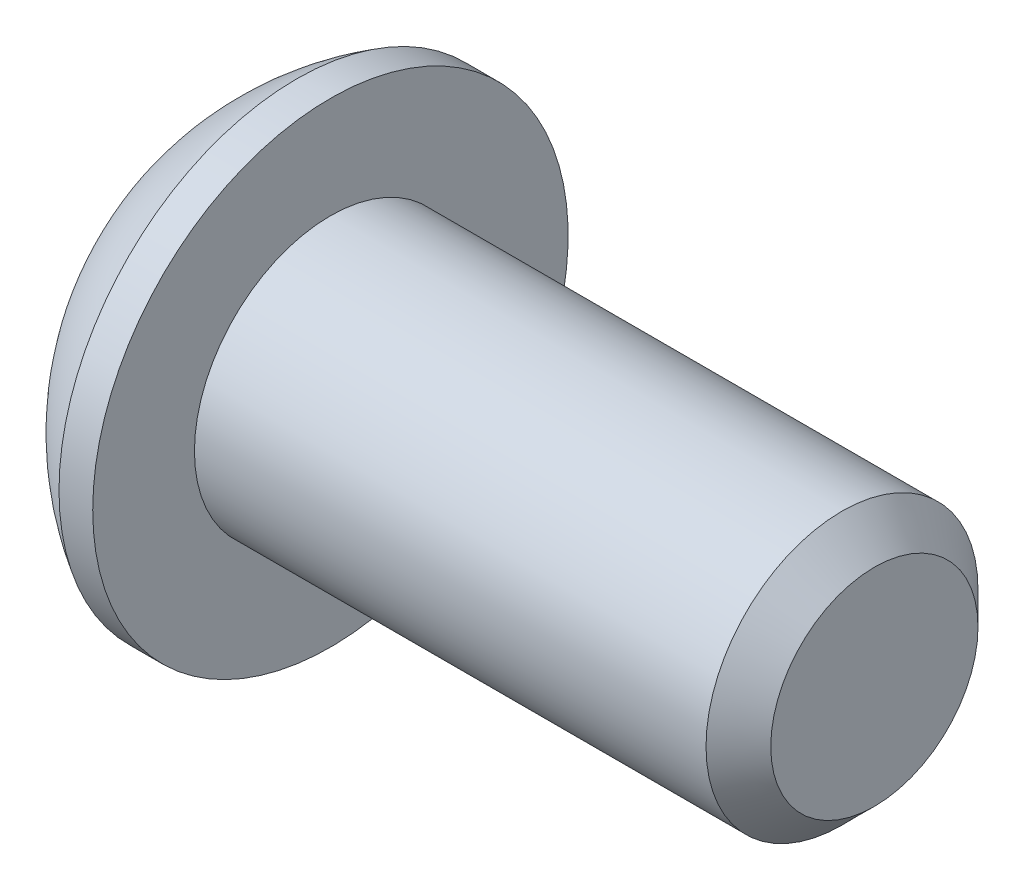
SolidWorks part; units mm, degrees
ref_plane "Plane1" through (0, 0, 0) normal (0, 0, 1) x (1, 0, 0)
ref_plane "Plane2" through (0, 0, 0) normal (0, 1, 0) x (1, 0, 0)
ref_plane "Plane3" through (0, 0, 0) normal (1, 0, 0) x (0, 0, -1)
sketch "BodySke" plane through (0, 0, 0) normal (0, 0, 1) x (1, 0, 0)
  line L0 (16.0528, 0) -> (16.0528, 2.4193)
  line L1 (15.2971, 3.175) -> (3.3528, 3.175)
  line L2 (3.3528, 3.175) -> (3.3528, 5.5499)
  line L3 (3.3528, 5.5499) -> (2.5654, 5.5499)
  line L4 (0, 0) -> (101.6, 0) construction
  line L5 (3.3528, -5.5499) -> (2.5654, -5.5499) construction
  line L6 (55.6768, -3.175) -> (3.3528, -3.175) construction
  line L7 (16.0528, 0) -> (0, 0)
  line L8 (0, 2.775) -> (0, -2.775) construction
  line L9 (0, 0) -> (0, 2.775)
  line L10 (16.0528, 2.4193) -> (15.2971, 3.175)
  line L11 (16.0528, -2.4193) -> (15.2971, -3.175) construction
  line L12 (4.6228, 9.525) -> (4.6228, -3.175) construction
  line L13 (3.3528, 9.525) -> (3.3528, -3.175) construction
  arc A1 (0, 2.775) -> (2.5654, 5.5499) centre (5.7851, 0) cw
  dimension "D1" = 5.5499
  dimension "Diameter" = 6.35
  dimension "Length" = 12.7
  dimension "Head_dia" = 11.0998
  dimension "Head_ht" = 3.3528
  dimension "Head_side_ht" = 0.7874
  dimension "Minor_dia" = 4.8387
  dimension "Body_ch_ang" = 45
  dimension "Advance" = 1.27
  dimension "Thread_nom" = 12.7
revolve "BaseBody" add sketch "BodySke" angle 360 about L4
cosmetic thread "ThreadCosmetic" [suppressed] parameters "Thread_length"=11.43, "Thread_minor"=4.8387
sketch "Sketch2" plane through (0, 0, 0) normal (0, 0, 1) x (1, 0, 0)
  line L0 (0, 1.9812) -> (2.2098, 1.9812)
  line L1 (2.2098, 1.9812) -> (3.3536, 0)
  line L3 (3.3536, 0) -> (0, 0)
  line L4 (0, 0) -> (0, 1.9812)
  line L5 (0, -1.9812) -> (2.2098, -1.9812) construction
  line L6 (0, 0) -> (47.625, 0) construction
  dimension "D2" = 60
  dimension "PreBroach_depth" = 2.2098
  dimension "PreBroach_dia" = 3.9624
revolve "PreBroach" cut sketch "Sketch2" angle 360 about L6
sketch "Sketch3" plane through (0, 0, 0) normal (1, 0, 0) x (0, 0, -1)
  line L0 (-1.9812, -1.1438) -> (-1.9812, 1.1438)
  line L1 (-1.9812, 1.1438) -> (0, 2.2877)
  line L2 (0, 2.2877) -> (1.9812, 1.1438)
  line L3 (1.9812, 1.1438) -> (1.9812, -1.1438)
  line L4 (1.9812, -1.1438) -> (0, -2.2877)
  line L5 (0, -2.2877) -> (-1.9812, -1.1438)
  dimension "D1" = 1.9812
  dimension "D2" = 1.9812
  dimension "D3" = 3.9624
  dimension "Hex_size" = 3.9624
extrude "Hex" cut sketch "Sketch3" along normal blind 2.2098
sketch "Sketch4" plane through (0, 9.525, 0) normal (1, 0, 0) x (0, 0, -1)
  line L0 (0, -9.525) -> (2.3876, -9.525)
  line L1 (0, -9.525) -> (6.1484, -5.9752) construction
  line L2 (0, -9.525) -> (1.1938, -7.4573)
  line L3 (1.9883, -8.949) -> (2.2704, -8.7861)
  line L4 (1.493, -8.0911) -> (1.7751, -7.9282)
  arc A0 (1.9883, -8.949) -> (1.493, -8.0911) centre (0, -9.525) ccw
  arc A1 (2.3876, -9.525) -> (2.2704, -8.7861) centre (0, -9.525) ccw
  arc A2 (1.1938, -7.4573) -> (1.7751, -7.9282) centre (0, -9.525) cw
  dimension "D1" = 30
  dimension "Spline_n_dim" = 4.1402
  dimension "Spline_m_dim" = 4.7752
  dimension "D2" = 60
  dimension "D3" = 0.4953
  dimension "Spline_p_dim" = 0.9906
extrude "Spline" [suppressed] cut sketch "Sketch4" along normal blind 2.2098
pattern_circular "CirPattern1" [suppressed] count 6 every 60 about axis through (0, 0, 0) along (1, 0, 0)
sketch "ThdSchSke" plane through (0, 0, 0) normal (0, 0, 1) x (1, 0, 0)
  line L0 (4.6228, -2.4193) -> (4.0937, -3.175)
  line L1 (4.6228, -2.4193) -> (5.1519, -3.175)
  line L2 (5.1519, -3.175) -> (5.1519, -3.9688)
  line L3 (-3.175, 0) -> (5.1513, 0) construction
  line L5 (5.1519, -3.9688) -> (4.0937, -3.9688)
  line L6 (4.0937, -3.9688) -> (4.0937, -3.175)
  dimension "Thread_minor" = 4.8387
  dimension "Diameter" = 6.35
  dimension "Start" = 4.6228
  dimension "SideAngle" = 55
  dimension "VeeAngle" = 70
  dimension "Overcut" = 7.9375
revolve "ThreadSchematic" [suppressed] cut sketch "ThdSchSke" angle 360 about L3
pattern_linear "ThdSchPat" [suppressed]
equation "\"D1@BodySke\" = \"Head_dia@BodySke\" * .5"
equation "\"Thread_minor@ThreadCosmetic\" = \"Minor_dia@BodySke\""
equation "\"D1@Sketch3\" = \"Hex_size@Sketch3\" / 2"
equation "\"D2@Sketch3\" = \"D1@Sketch3\""
equation "\"D3@Sketch3\" = \"Hex_size@Sketch3\""
equation "\"D3@Sketch4\" = \"Spline_p_dim@Sketch4\" / 2"
equation "\"D1@Sketch4\" = \"D2@Sketch4\" / 2"
equation "\"Thread_length@ThreadCosmetic\" = ((sgn( (\"Length@BodySke\" - \"Advance@BodySke\" ) - \"Thread_nom@BodySke\" )-1)*( (\"Length@BodySke\" - \"Advance@BodySke\" ) - \"Thread_nom@BodySke\" ))/-2+ \"Thread_nom@BodySke\""
equation "\"Thread_minor@ThdSchSke\" = \"Minor_dia@BodySke\""
equation "\"Diameter@ThdSchSke\" = \"Diameter@BodySke\""
equation "\"Overcut@ThdSchSke\" = \"Diameter@BodySke\" * 1.25"
equation "\"Start@ThdSchSke\" = \"Head_ht@BodySke\" + \"Length@BodySke\" - \"Thread_length@ThreadCosmetic\"  '---Non-countersunk---"
equation "\"Num_threads@ThdSchPat\" = int( \"Thread_length@ThreadCosmetic\" / \"Advance@BodySke\" + 0.999 )  + 1"
equation "\"Advance@ThdSchPat\" = \"Thread_length@ThreadCosmetic\" /  (\"Num_threads@ThdSchPat\" - 1) 'relax it"
equation "\"Num_threads@ThdSchPat\" = \"Num_threads@ThdSchPat\" - sgn( \"Num_threads@ThdSchPat\" - 1) '---chamfered tips only---"
